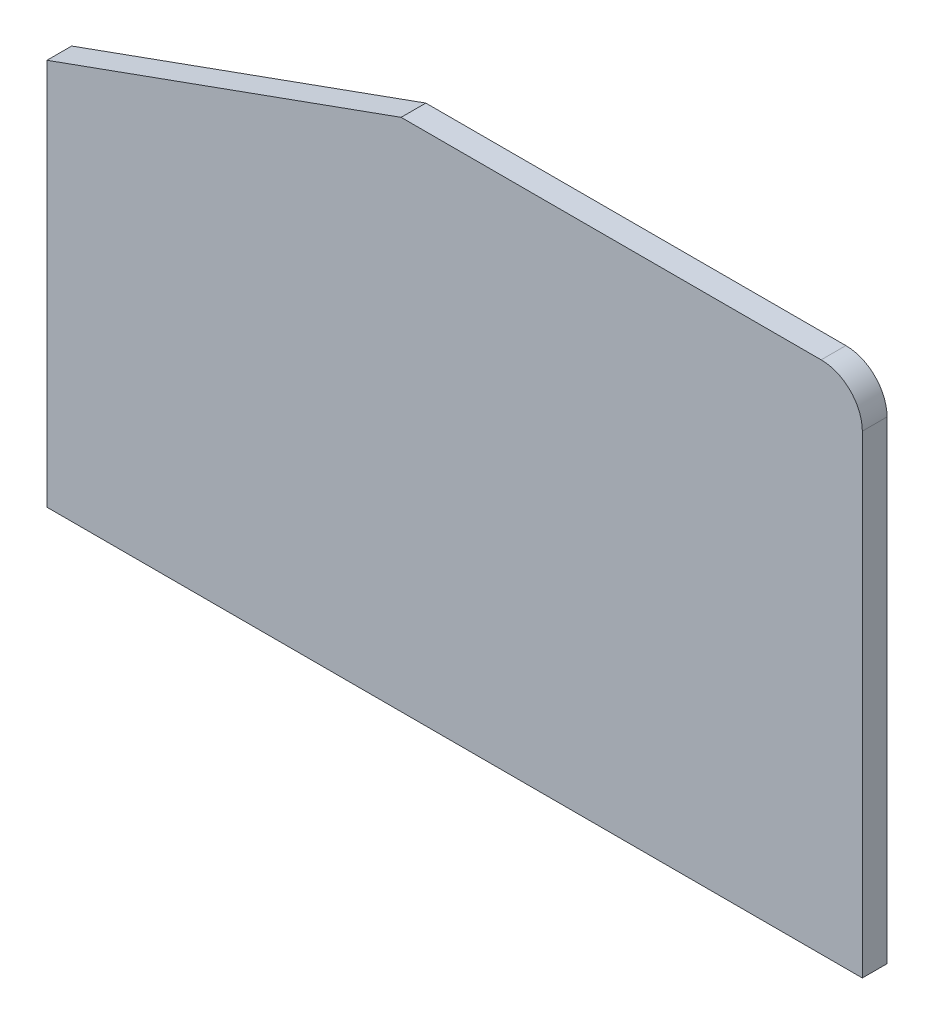
SolidWorks part; units mm, degrees
material "ASTM A36 Steel"
ref_plane "Front Plane" through (0, 0, 0) normal (0, 0, 1) x (1, 0, 0)
ref_plane "Top Plane" through (0, 0, 0) normal (0, 1, 0) x (1, 0, 0)
ref_plane "Right Plane" through (0, 0, 0) normal (1, 0, 0) x (0, 0, -1)
sketch "Sketch1" plane through (0, 0, 0) normal (0, 0, 1) x (1, 0, 0)
  line L0 (-99, 31.5) -> (-13, 62.5)
  line L1 (-99, -62.5) -> (99, -62.5)
  line L2 (-99, -62.5) -> (-99, 31.5)
  line L3 (-13, 62.5) -> (99, 62.5)
  line L4 (99, -62.5) -> (99, 62.5)
  line L5 (-99, -62.5) -> (99, 62.5) construction
  line L6 (-67.743, 42.7671) -> (99, -62.5) construction
  point P0 (0, 0)
  dimension "D1" = 198
  dimension "D2" = 125
  dimension "D3" = 94
  dimension "D4" = 112
extrude "Boss-Extrude1" add sketch "Sketch1" along normal mid plane 6
fillet "Fillet1" radius 10 1 edges at (99, 62.5, 0)
